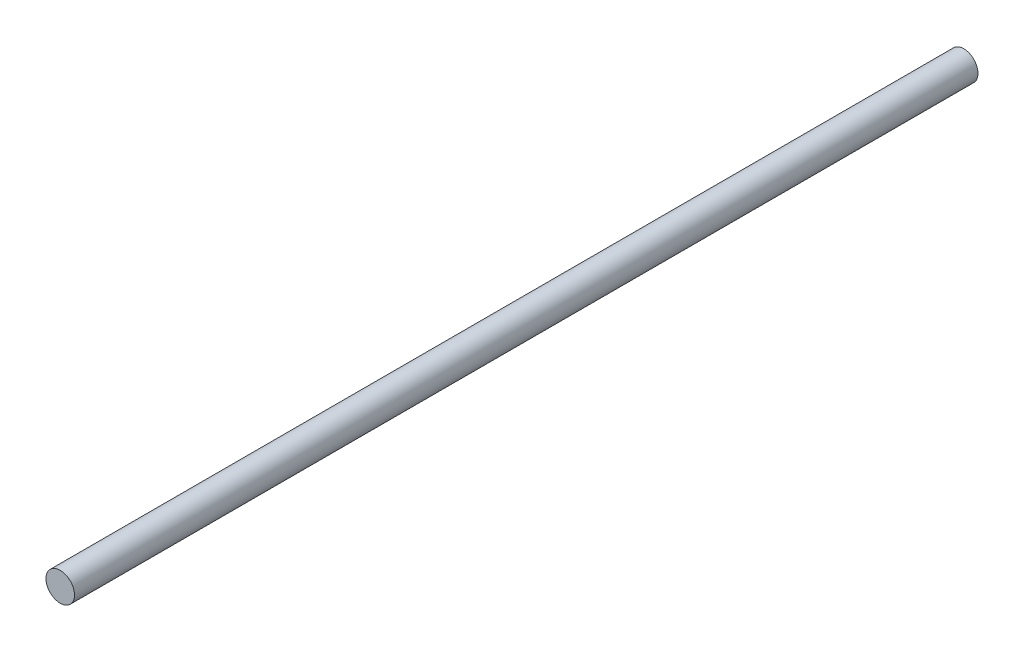
SolidWorks part; units mm, degrees
ref_plane "前视基准面" through (0, 0, 0) normal (0, 0, 1) x (1, 0, 0)
ref_plane "上视基准面" through (0, 0, 0) normal (0, 1, 0) x (1, 0, 0)
ref_plane "右视基准面" through (0, 0, 0) normal (1, 0, 0) x (0, 0, -1)
other "Configuration Table"
sketch "草图1" plane through (0, 0, 0) normal (0, 0, 1) x (1, 0, 0)
  circle A0 centre (0, 0) radius 3
  dimension "D1" = 6
extrude "凸台-拉伸1" add sketch "草图1" along normal blind 190
